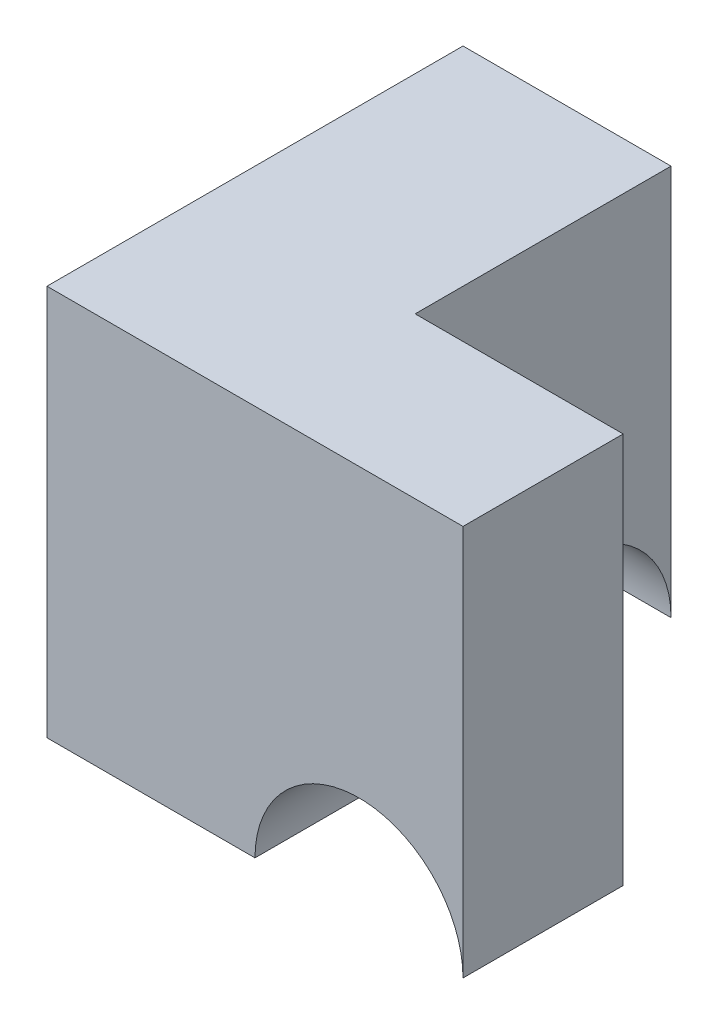
SolidWorks part; units mm, degrees
ref_plane "Front Plane" through (0, 0, 0) normal (0, 0, 1) x (1, 0, 0)
ref_plane "Top Plane" through (0, 0, 0) normal (0, 1, 0) x (1, 0, 0)
ref_plane "Right Plane" through (0, 0, 0) normal (1, 0, 0) x (0, 0, -1)
sketch "Sketch1" plane through (0, 0, 0) normal (0, 1, 0) x (1, 0, 0)
  line L1 (0, 0) -> (25, 0)
  line L2 (0, 0) -> (0, -19.2469)
  line L3 (0, -19.2469) -> (25, -19.2469)
  line L4 (25, 0) -> (25, -19.2469)
  line L5 (0, -19.2469) -> (-25, -19.2469)
  line L6 (0, -19.2469) -> (0, 30.7531)
  line L7 (0, 30.7531) -> (-25, 30.7531)
  line L8 (-25, -19.2469) -> (-25, 30.7531)
  point P10 (-23.8935, -30.9753)
  dimension "D1" = 50
  dimension "D2" = 25
  dimension "D3" = 25
extrude "Boss-Extrude1" add sketch "Sketch1" along normal blind 47 contours L8 L5 L2 L6 L7 | L4 L1 L2 L3
sketch "Sketch2" plane through (0, 0, 19.2469) normal (0, 0, 1) x (1, 0, 0)
  line L0 (25, 0) -> (-25, 0) construction
  arc A0 (25, 0) -> (0, 0) centre (12.5, 0) ccw
  dimension "D1" = 12.5
extrude "Cut-Extrude1" cut sketch "Sketch2" against normal blind 50 and the other way through all
sketch "Sketch3" plane through (-25, 0, 0) normal (-1, 0, 0) x (0, 0, 1)
  circle A0 centre (-18.2531, 0) radius 12.5
  dimension "D1" = 25
extrude "Cut-Extrude2" cut sketch "Sketch3" against normal blind 50
